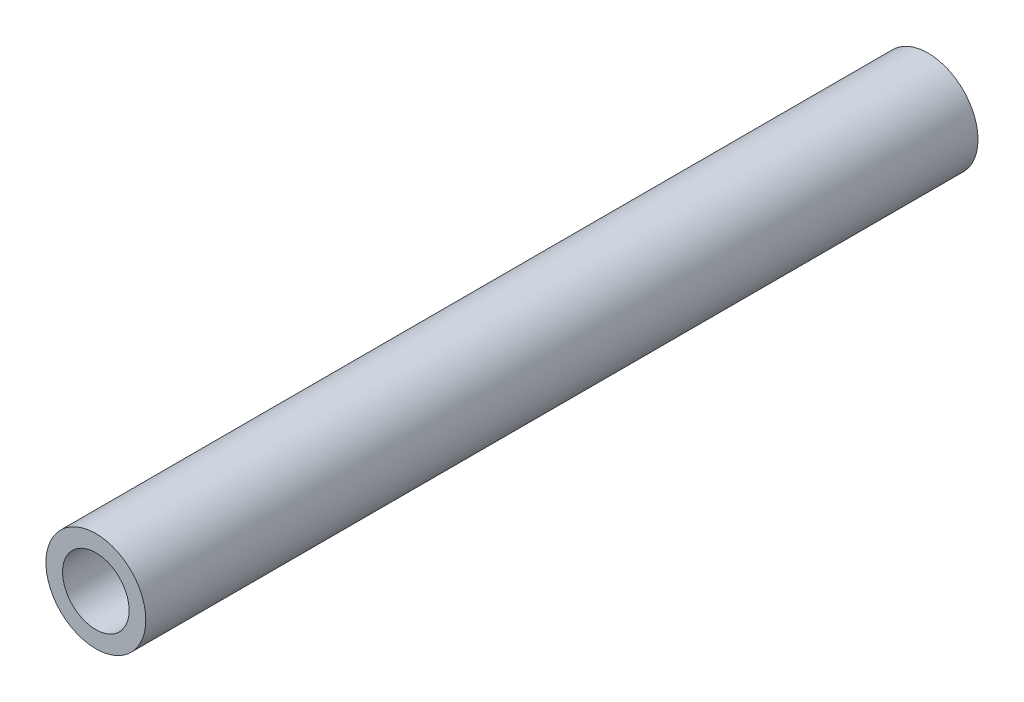
SolidWorks part; units mm, degrees
ref_plane "Plan de face" through (0, 0, 0) normal (0, 0, 1) x (1, 0, 0)
ref_plane "Plan de dessus" through (0, 0, 0) normal (0, 1, 0) x (1, 0, 0)
ref_plane "Plan de droite" through (0, 0, 0) normal (1, 0, 0) x (0, 0, -1)
sketch "Esquisse1" plane through (0, 0, 0) normal (0, 0, 1) x (1, 0, 0)
  circle A0 centre (0, 0) radius 3
  dimension "D1" = 6
extrude "Boss.-Extru.1" add sketch "Esquisse1" along normal blind 50
sketch "Esquisse2" plane through (0, 0, 0) normal (0, 0, -1) x (-1, 0, 0)
  circle A0 centre (0, 0) radius 2
extrude "Enlèv. mat.-Extru.1" cut sketch "Esquisse2" against normal through all contours A0
